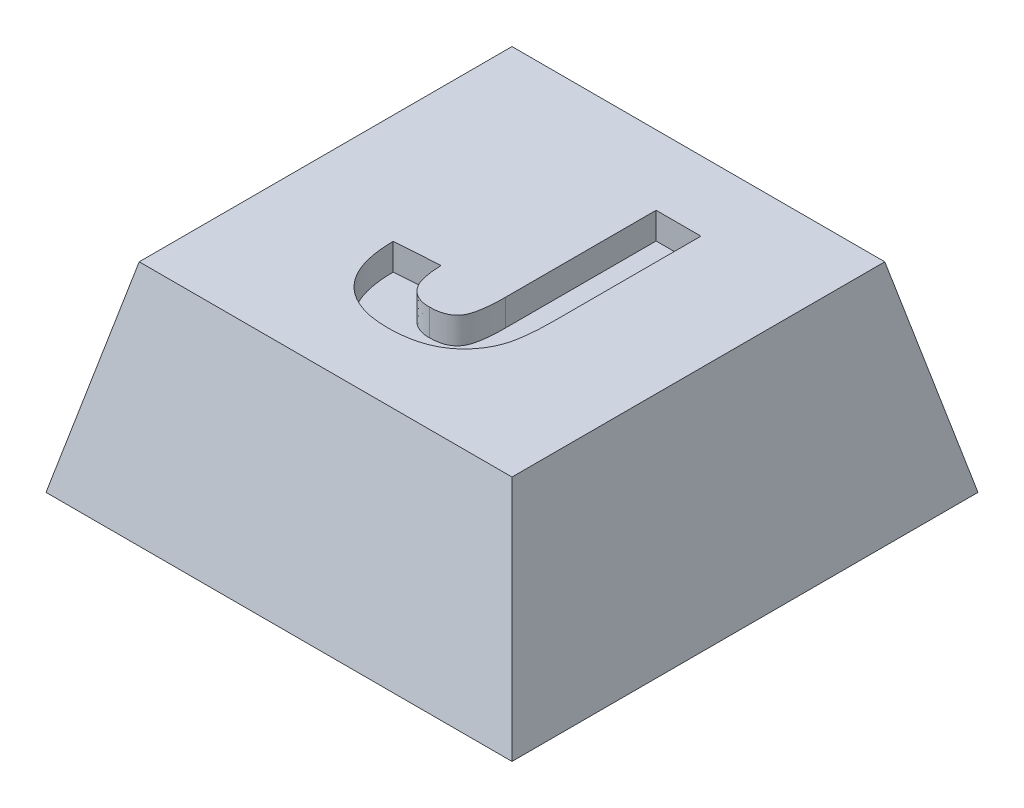
SolidWorks part; units mm, degrees
ref_plane "Front Plane" through (0, 0, 0) normal (0, 0, 1) x (1, 0, 0)
ref_plane "Top Plane" through (0, 0, 0) normal (0, 1, 0) x (1, 0, 0)
ref_plane "Right Plane" through (0, 0, 0) normal (1, 0, 0) x (0, 0, -1)
sketch "Sketch1" plane through (0, 0, 0) normal (0, 1, 0) x (1, 0, 0)
  line L1 (0, 0) -> (7, 0)
  line L2 (0, 0) -> (0, 7)
  line L3 (0, 7) -> (7, 7)
  line L4 (7, 0) -> (7, 7)
  dimension "D1" = 7
  dimension "D2" = 7
extrude "Boss-Extrude1" add sketch "Sketch1" along normal blind 3
sketch "Sketch2" plane through (0, 0, 0) normal (0, 0, 1) x (1, 0, 0)
  line L0 (0, 0) -> (0.7, 3)
  line L1 (0, 3) -> (7, 3) construction
  line L2 (0.7, 3) -> (0, 3)
  line L3 (0, 3) -> (0, 0)
  line L4 (7, 0) -> (6.3, 3)
  line L5 (6.3, 3) -> (7, 3)
  line L6 (7, 3) -> (7, 0)
  dimension "D1" = 0.7
  dimension "D2" = 0.7
extrude "Cut-Extrude1" cut sketch "Sketch2" against normal blind 7
sketch "Sketch3" plane through (0, 0, 0) normal (1, 0, 0) x (0, 0, -1)
  line L0 (0, 0) -> (0.7, 3)
  line L1 (7, 3) -> (0, 3) construction
  line L2 (0.7, 3) -> (0, 3)
  line L3 (0, 3) -> (0, 0)
  line L4 (7, 3) -> (6.3, 3)
  line L5 (6.3, 3) -> (7, 0)
  line L6 (7, 3) -> (7, 0)
  dimension "D1" = 0.7
  dimension "D2" = 0.7
extrude "Cut-Extrude2" cut sketch "Sketch3" along normal blind 11
sketch "Sketch4" plane through (0, 0, 0) normal (0, -1, 0) x (1, 0, 0)
  line L0 (3.5, 0) -> (3.5, -7) construction
  line L1 (0, 0) -> (7, 0) construction
  line L2 (7, -7) -> (0, -7) construction
  line L3 (0, -3.5) -> (7, -3.5) construction
  line L4 (0, -7) -> (0, 0) construction
  line L5 (7, 0) -> (7, -7) construction
  circle A0 centre (3.5, -3.5) radius 1.8
  dimension "D1" = 3.6
extrude "Cut-Extrude3" cut sketch "Sketch4" against normal blind 0.8
sketch "Sketch5" plane through (0, 3, 0) normal (0, 1, 0) x (1, 0, 0)
  text T0 "J" font "Arial" height 3.5
extrude "Cut-Extrude4" cut sketch "Sketch5" against normal blind 0.4
